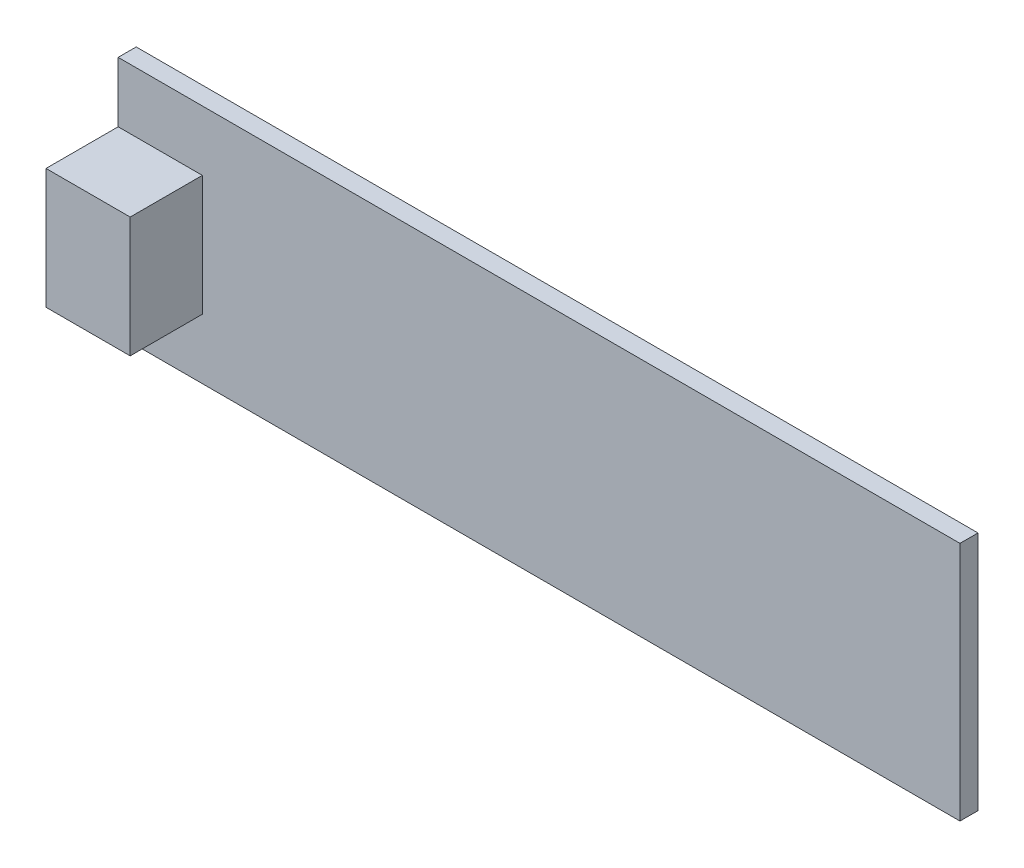
SolidWorks part; units mm, degrees
material "PLA"
ref_plane "Front Plane" through (0, 0, 0) normal (0, 0, 1) x (1, 0, 0)
ref_plane "Top Plane" through (0, 0, 0) normal (0, 1, 0) x (1, 0, 0)
ref_plane "Right Plane" through (0, 0, 0) normal (1, 0, 0) x (0, 0, -1)
sketch "Sketch1" plane through (0, 0, 0) normal (0, 0, 1) x (1, 0, 0)
  line L1 (-35, -10) -> (35, -10)
  line L2 (-35, -10) -> (-35, 10)
  line L3 (-35, 10) -> (35, 10)
  line L4 (35, -10) -> (35, 10)
  line L5 (-35, -10) -> (35, 10) construction
  line L6 (-35, 10) -> (35, -10) construction
  point P0 (0, 0)
  dimension "D1" = 70
  dimension "D2" = 20
extrude "Boss-Extrude1" add sketch "Sketch1" along normal mid plane 1.5
sketch "Sketch2" plane through (0, 0, 0.75) normal (0, 0, 1) x (1, 0, 0)
  line L0 (-35, 10) -> (-35, -10) construction
  line L1 (-28, -5) -> (-35, -5)
  line L2 (-28, -5) -> (-28, 5)
  line L3 (-28, 5) -> (-35, 5)
  line L4 (-35, -5) -> (-35, 5)
  line L5 (-28, -5) -> (-35, 5) construction
  line L6 (-28, 5) -> (-35, -5) construction
  point P0 (-31.5, 0)
  dimension "D1" = 10
  dimension "D2" = 7
extrude "Boss-Extrude2" add sketch "Sketch2" along normal blind 6
